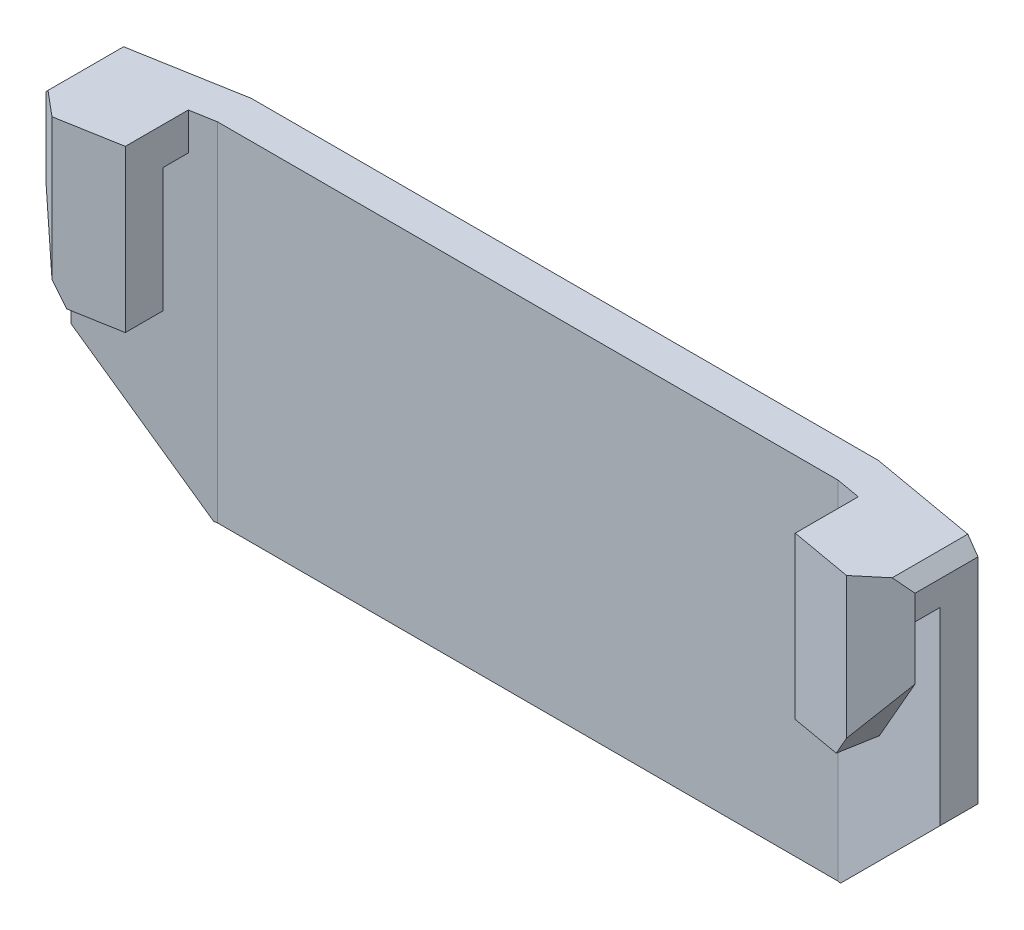
SolidWorks part; units mm, degrees
ref_plane "Front Plane" through (0, 0, 0) normal (0, 0, 1) x (1, 0, 0)
ref_plane "Top Plane" through (0, 0, 0) normal (0, 1, 0) x (1, 0, 0)
ref_plane "Right Plane" through (0, 0, 0) normal (1, 0, 0) x (0, 0, -1)
sketch "Sketch12" plane through (0, 0, 0) normal (0, 1, 0) x (1, 0, 0)
  line L24 (-27, -6.4144) -> (-27, -2.3527)
  line L25 (-27, -2.3527) -> (-25, -2)
  line L26 (35.0231, -1.7365) -> (25.175, 0)
  line L27 (25.175, 0) -> (-25.175, 0)
  line L28 (-25.175, 0) -> (-35.0231, -1.7365)
  line L29 (-25, -2) -> (25, -2)
  line L30 (35.0231, -7.829) -> (27, -6.4144)
  line L31 (27, -6.4144) -> (27, -2.3527)
  line L32 (-35.0231, -7.829) -> (-27, -6.4144)
  line L33 (-35.0231, -1.7365) -> (-35.0231, -7.829)
  line L34 (35.0231, -1.7365) -> (35.0231, -7.829)
  line L35 (27, -2.3527) -> (25, -2)
  point P12 (0, 0)
  dimension "D1" = 25
  dimension "D2" = 25.175
  dimension "D3" = 27
  dimension "D4" = 35.0231
  dimension "D5" = 1.7365
  dimension "D6" = 2
  dimension "D7" = 6.4144
extrude "Boss-Extrude1" add sketch "Sketch12" along normal blind 3
sketch "Sketch13" plane through (0, 0, 0) normal (0, -1, 0) x (1, 0, 0)
  line L0 (25.175, 0) -> (35.0231, 1.7365)
  line L1 (25.175, 0) -> (-25.175, 0)
  line L2 (-25.175, 0) -> (-35.0231, 1.7365)
  line L3 (25, 2) -> (27, 2.3527)
  line L5 (-25, 2) -> (25, 2)
  line L6 (27, 2.3527) -> (35.0231, 3.7673)
  line L7 (35.0231, 7.829) -> (35.0231, 1.7365) construction
  line L9 (35.0231, 3.7673) -> (35.0231, 1.7365)
  line L10 (-25, 2) -> (-27, 2.3527)
  line L11 (-27, 2.3527) -> (-35.0231, 3.7673)
  line L12 (-35.0231, 1.7365) -> (-35.0231, 7.829) construction
  line L13 (-35.0231, 3.7673) -> (-35.0231, 1.7365)
extrude "Boss-Extrude2" add sketch "Sketch13" along normal blind 25
sketch "Sketch14" plane through (0, 0, 0) normal (0, -1, 0) x (1, 0, 0)
  line L6 (-35.0231, 5.7982) -> (-27, 4.3835)
  line L13 (-35.0231, 3.7673) -> (-35.0231, 7.829) construction
  line L14 (-27, 6.4144) -> (-27, 2.3527) construction
  line L15 (-27, 4.3835) -> (-27, 7.4298)
  line L16 (-27, 7.4298) -> (-35.0231, 8.8445)
  line L17 (-35.0231, 8.8445) -> (-35.0231, 5.7982)
  line L18 (-35.0231, 7.829) -> (-27, 6.4144) construction
  line L19 (0, 2) -> (0, 0) construction
  line L20 (25, 2) -> (-25, 2) construction
  line L21 (27, 7.4298) -> (35.0231, 8.8445)
  line L22 (27, 4.3835) -> (27, 7.4298)
  line L23 (35.0231, 5.7982) -> (27, 4.3835)
  line L24 (35.0231, 8.8445) -> (35.0231, 5.7982)
  dimension "D1" = 3
  dimension "D3" = 1
extrude "Boss-Extrude3" add sketch "Sketch14" along normal blind 10 and the other way up to surface
sketch "Sketch24" plane through (0, 3, 0) normal (0, 1, 0) x (1, 0, 0)
  line L1 (-35.0231, -0.7211) -> (-25.2625, 1)
  line L2 (-25.2625, 1) -> (25.2625, 1)
  line L3 (25.2625, 1) -> (35.0231, -0.7211)
  line L6 (25.175, 0) -> (-25.175, 0)
  line L9 (-35.0231, -0.7211) -> (-35.0231, -1.7365)
  line L10 (-35.0231, -1.7365) -> (-25.175, 0)
  line L11 (35.0231, -0.7211) -> (35.0231, -1.7365)
  line L12 (35.0231, -1.7365) -> (25.175, 0)
  point P0 (-30.1428, 0.1395)
  dimension "D1" = 1
  dimension "D2" = 1
  dimension "D3" = 1
extrude "Boss-Extrude5" add sketch "Sketch24" against normal up to surface (28 mm away) up to face at (0, -25, 1.876)
sketch "Sketch26" plane through (0, 0, -1) normal (0, 0, -1) x (-1, 0, 0)
  line L0 (-25.2625, -25) -> (-35.0231, -25)
  line L1 (-35.0231, -25) -> (-35.0231, -15.2394)
  line L2 (-35.0231, -25) -> (-35.0231, 3) construction
  line L3 (-35.0231, -15.2394) -> (-25.2625, -25)
  line L5 (25.2625, -25) -> (35.0231, -15.2394)
  line L6 (35.0231, -25) -> (35.0231, 3) construction
  line L7 (35.0231, -15.2394) -> (35.0231, -25)
  line L8 (35.0231, -25) -> (25.2625, -25)
  line L9 (-25.2625, -25) -> (25.2625, -25) construction
  dimension "D1" = 135
  dimension "D2" = 135
extrude "Cut-Extrude9" cut sketch "Sketch26" against normal up to vertex
sketch "Sketch27" plane through (0.4564, 0, 2.5885) normal (0.1736, 0, 0.9848) x (0.9848, 0, -0.1736)
  line L0 (-36.0268, -3.5) -> (-31.9534, -10)
  line L1 (-36.0268, 3) -> (-36.0268, -10) construction
  line L2 (-27.88, -10) -> (-36.0268, -10) construction
  line L3 (-31.9534, -10) -> (-36.0268, -10)
  line L4 (-36.0268, -10) -> (-36.0268, -3.5)
extrude "Cut-Extrude10" cut sketch "Sketch27" against normal up to surface (3 mm away) up to face at (-31.0115, -5, 5.0908)
sketch "Sketch28" plane through (-0.4564, 0, 2.5885) normal (-0.1736, 0, 0.9848) x (0.9848, 0, 0.1736)
  line L0 (36.0268, -3.5) -> (31.9534, -10)
  line L1 (36.0268, 3) -> (36.0268, -10) construction
  line L2 (36.0268, -10) -> (27.88, -10) construction
  line L3 (31.9534, -10) -> (36.0268, -10)
  line L4 (36.0268, -10) -> (36.0268, -3.5)
extrude "Cut-Extrude11" cut sketch "Sketch28" against normal up to surface (3 mm away) up to face at (31.0115, -5, 5.0908)
chamfer "Chamfer2" [suppressed] distance 3.2 angle 45
chamfer "Chamfer3" [suppressed] distance 3.1 angle 50
sketch "Sketch31" plane through (0, -10, 0) normal (0, -1, 0) x (1, 0, 0)
  line L0 (35.0231, 5.7982) -> (32.0231, 8.3155)
  line L1 (35.0231, 8.8445) -> (31.0115, 8.1371) construction
  line L2 (32.0231, 8.3155) -> (35.0231, 8.8445)
  line L3 (35.0231, 8.8445) -> (35.0231, 5.7982)
  dimension "D1" = 130
extrude "Cut-Extrude14" cut sketch "Sketch31" against normal up to surface (13 mm away)
sketch "Sketch33" plane through (0, -10, 0) normal (0, -1, 0) x (1, 0, 0)
  line L0 (-35.0231, 5.7982) -> (-32.0231, 8.3155)
  line L1 (-31.0115, 8.1371) -> (-35.0231, 8.8445) construction
  line L2 (-32.0231, 8.3155) -> (-35.0231, 8.8445)
  line L3 (-35.0231, 8.8445) -> (-35.0231, 5.7982)
  line L4 (-27, 7.4298) -> (-31.0115, 8.1371) construction
  dimension "D1" = 130
extrude "Cut-Extrude15" cut sketch "Sketch33" against normal up to surface (13 mm away)
chamfer "Chamfer4" distance 1 angle 45 2 edges at (-35.0231, 3, 3.2596) (35.0231, 3, 3.2596)
